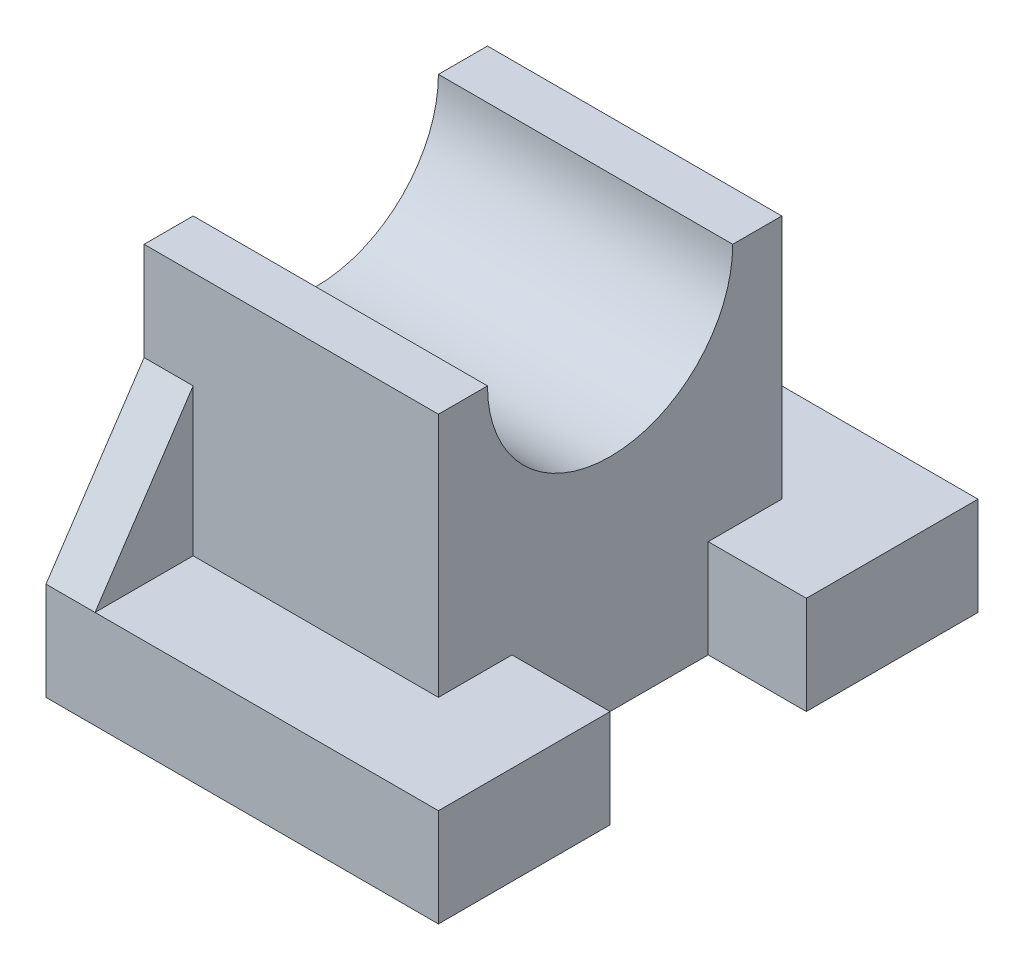
SolidWorks part; units mm, degrees
ref_plane "Спереди" through (0, 0, 0) normal (0, 0, 1) x (1, 0, 0)
ref_plane "Сверху" through (0, 0, 0) normal (0, 1, 0) x (1, 0, 0)
ref_plane "Справа" through (0, 0, 0) normal (1, 0, 0) x (0, 0, -1)
sketch "Эскиз3" plane through (0, 0, 0) normal (0, 1, 0) x (1, 0, 0)
  line L1 (40, 55) -> (-40, 55)
  line L2 (40, 55) -> (40, -55)
  line L3 (40, -55) -> (-40, -55)
  line L4 (-40, 55) -> (-40, -55)
  line L5 (40, 55) -> (-40, -55) construction
  line L6 (40, -55) -> (-40, 55) construction
  point P0 (0, 0)
  dimension "D1" = 110
  dimension "D2" = 80
extrude "Бобышка-Вытянуть2" add sketch "Эскиз3" along normal blind 20
sketch "Эскиз4" plane through (0, 0, 0) normal (0, 1, 0) x (1, 0, 0)
  line L1 (-40, 35) -> (20, 35)
  line L2 (-40, 35) -> (-40, -35)
  line L3 (-40, -35) -> (20, -35)
  line L4 (-40, -55) -> (40, -55) construction
  line L5 (20, -55) -> (-40, -55) construction
  line L6 (20, 35) -> (20, -35)
  line L7 (-40, -35) -> (20, -35) construction
  line L8 (20, -35) -> (20, 35) construction
  line L9 (20, 35) -> (-40, 35) construction
  dimension "D1" = 20
  dimension "D2" = 35
  dimension "D3" = 35
extrude "Бобышка-Вытянуть3" add sketch "Эскиз4" along normal blind 70
sketch "Эскиз5" plane through (0, 0, 0) normal (0, 1, 0) x (1, 0, 0)
  line L0 (-40, -55) -> (40, -55) construction
  line L1 (-40, 55) -> (-30, 55)
  line L2 (-40, 55) -> (-40, -55)
  line L3 (-40, -55) -> (-30, -55)
  line L4 (-30, 55) -> (-30, -55)
  dimension "D1" = 30
extrude "Бобышка-Вытянуть4" add sketch "Эскиз5" along normal blind 50
sketch "Эскиз6" plane through (0, 0, 0) normal (0, 1, 0) x (1, 0, 0)
  line L1 (20, 20) -> (40, 20)
  line L2 (40, 20) -> (20, 20) construction
  line L3 (20, -35) -> (20, 35) construction
  line L4 (20, 20) -> (20, -20) construction
  line L5 (20, -20) -> (40, -20) construction
  line L6 (20, 20) -> (20, -20)
  line L7 (20, -20) -> (40, -20)
  line L8 (40, 20) -> (40, -20)
  dimension "D1" = 40
  dimension "D2" = 20
  dimension "D3" = 20
extrude "Вырез-Вытянуть1" cut sketch "Эскиз6" along normal through all
sketch "Эскиз7" plane through (0, 0, 0) normal (1, 0, 0) x (0, 0, -1)
  line L0 (-55, 20) -> (-35, 50)
  line L1 (-35, 50) -> (-55, 50)
  line L2 (-55, 50) -> (-55, 20)
  line L3 (55, 20) -> (35, 50)
  line L4 (35, 50) -> (55, 50)
  line L5 (55, 50) -> (55, 20)
extrude "Вырез-Вытянуть2" cut sketch "Эскиз7" against normal through all
sketch "Эскиз8" plane through (0, 0, 0) normal (1, 0, 0) x (0, 0, -1)
  line L0 (-35, 70) -> (35, 70) construction
  circle A0 centre (0, 70) radius 25
  dimension "D1" = 50
extrude "Вырез-Вытянуть3" cut sketch "Эскиз8" against normal through all both and the other way through all
